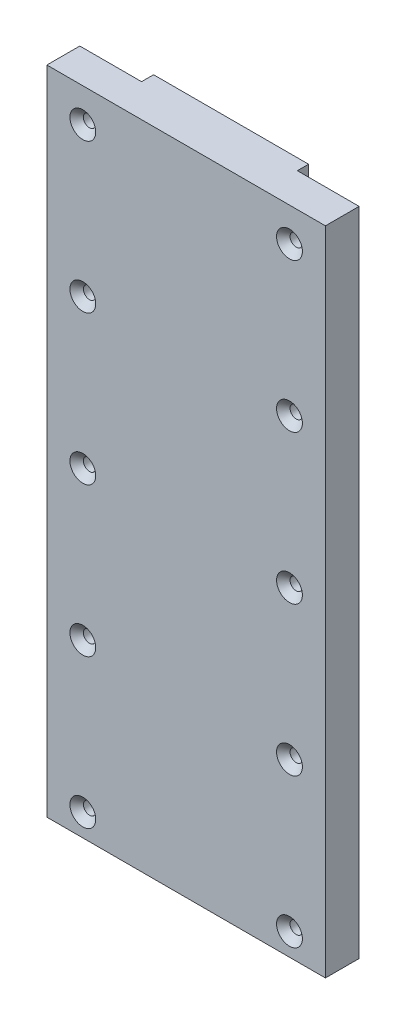
SolidWorks part; units mm, degrees
ref_plane "Front Plane" through (0, 0, 0) normal (1, 0, 0) x (0, 1, 0)
ref_plane "Top Plane" through (0, 0, 0) normal (0, 0, 1) x (0, 1, 0)
ref_plane "Right Plane" through (0, 0, 0) normal (0, 1, 0) x (-1, 0, 0)
sketch "Sketch2" plane through (0, 0, 0) normal (0, 0, 1) x (0, 1, 0)
  line L1 (290, 124) -> (-290, 124)
  line L2 (290, 124) -> (290, -124)
  line L3 (290, -124) -> (-290, -124)
  line L4 (-290, 124) -> (-290, -124)
  line L5 (290, 124) -> (-290, -124) construction
  line L6 (290, -124) -> (-290, 124) construction
  point P0 (0, 0)
  dimension "D1" = 580
  dimension "D2" = 248
extrude "Boss-Extrude1" add sketch "Sketch2" along normal mid plane 40
sketch "Sketch3" plane through (0, 290, 0) normal (0, 1, 0) x (-1, 0, 0)
  line L1 (124, -20) -> (69, -20)
  line L2 (124, -20) -> (124, -9.2932)
  line L3 (124, -9.2932) -> (69, -9.2932)
  line L4 (69, -20) -> (69, -9.2932)
  line L5 (-124, -20) -> (-69, -20)
  line L6 (-124, -20) -> (-124, -10)
  line L7 (-124, -10) -> (-69, -10)
  line L8 (-69, -20) -> (-69, -10)
  dimension "D1" = 10
  dimension "D2" = 138
extrude "Cut-Extrude1" cut sketch "Sketch3" against normal through all
sketch "Sketch4" plane through (0, 0, 20) normal (0, 0, 1) x (1, 0, 0)
  line L0 (-124, -290) -> (124, -290) construction
  line L3 (-92, -270) -> (-124, -270)
  line L4 (-124, 290) -> (-124, -290) construction
  line L5 (92, -270) -> (124, -270)
  line L6 (124, -290) -> (124, 290) construction
  point P0 (92, -270)
  point P1 (-92, -270)
  dimension "D1" = 184
  dimension "D2" = 20
hole_wizard "Ø11.0 (11) Diameter Hole1" positions "3DSketch1" profile "Sketch6" hole size "Ø11.0" standard "ISO" end condition through all
sketch3d "3DSketch1"
  point P0 (-92, -270, 20)
  point P3 (92, -270, 20)
sketch "Sketch6" plane through (-92, -270, 20) normal (1, 0, 0) x (0, -1, 0)
  line L0 (0, 0) -> (0, 40)
  line L1 (0, 40) -> (5.5, 40)
  line L2 (5.5, 40) -> (5.5, 0)
  line L5 (5.5, 0) -> (0, 0)
  line L11 (0, -6.35) -> (0, 107.95) construction
  dimension "Thru Hole Dia." = 11
  dimension "Thru Hole Depth" = 40
pattern_linear "LPattern1" count 5 spacing 132.5 along (0, 1, 0) of "Ø11.0 (11) Diameter Hole1"
chamfer "Chamfer1" distance 6 angle 45 10 edges at (97.5, 260, 20) (-86.5, 260, 20) (-86.5, 127.5, 20) (97.5, 127.5, 20) (-86.5, -5, 20) (97.5, -5, 20) (97.5, -137.5, 20) (-86.5, -137.5, 20) (-86.5, -270, 20) (97.5, -270, 20)
